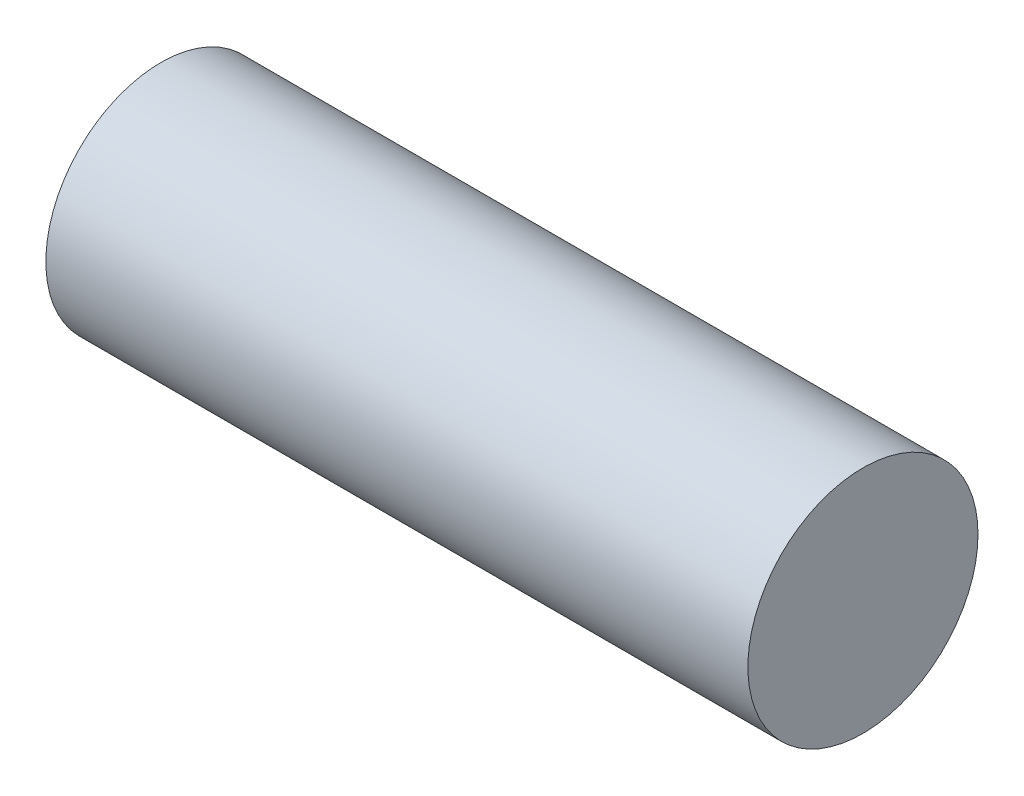
SolidWorks part; units mm, degrees
ref_plane "Front Plane" through (0, 0, 0) normal (0, 0, 1) x (1, 0, 0)
ref_plane "Top Plane" through (0, 0, 0) normal (0, 1, 0) x (1, 0, 0)
ref_plane "Right Plane" through (0, 0, 0) normal (1, 0, 0) x (0, 0, -1)
sketch "Sketch1" plane through (0, 0, 0) normal (1, 0, 0) x (0, 0, -1)
  circle A0 centre (0, 0) radius 2.95
  dimension "D1" = 5.9
extrude "Boss-Extrude1" add sketch "Sketch1" along normal blind 18
